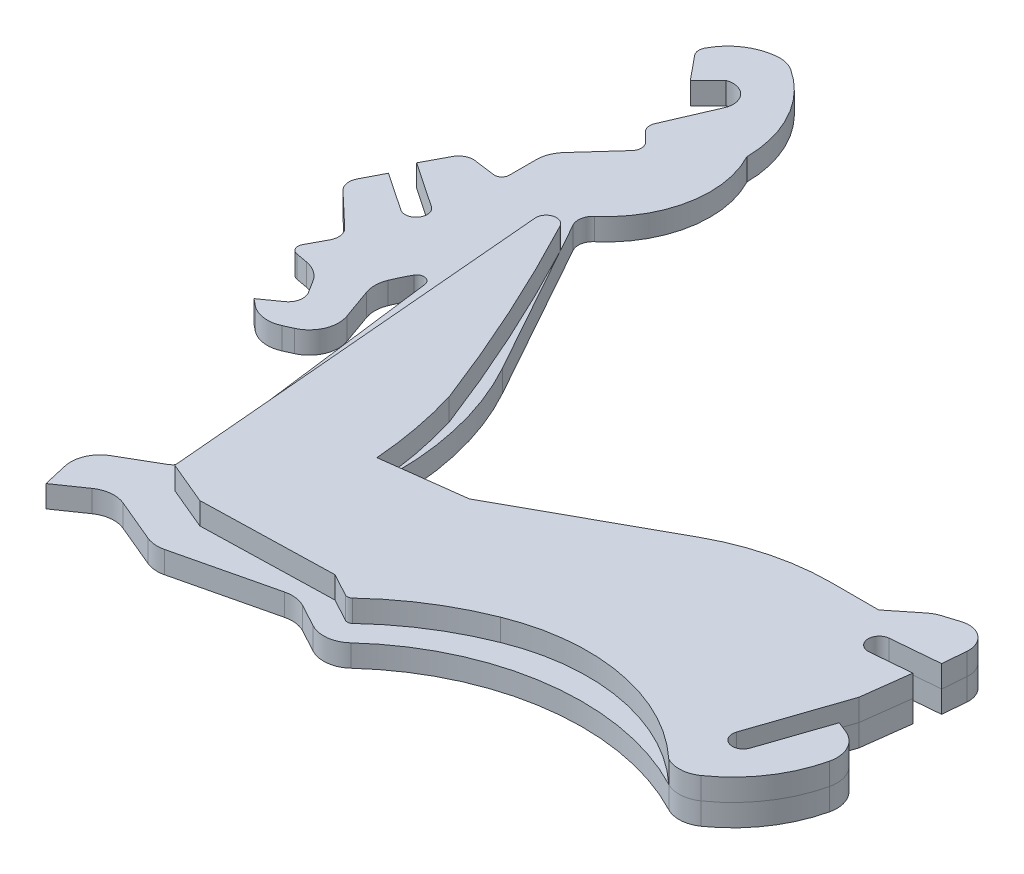
SolidWorks part; units mm, degrees
ref_plane "Front Plane" through (0, 0, 0) normal (0, 0, 1) x (1, 0, 0)
ref_plane "Top Plane" through (0, 0, 0) normal (0, 1, 0) x (1, 0, 0)
ref_plane "Right Plane" through (0, 0, 0) normal (1, 0, 0) x (0, 0, -1)
sketch "Sketch2" plane through (0, 0, 0) normal (0, 1, 0) x (1, 0, 0)
  line L0 (104.8617, 51.61) -> (96.2857, 51.61)
  line L1 (96.2857, 48.61) -> (104.8617, 48.61)
  line L2 (104.8617, 48.61) -> (104.8617, 42.36)
  line L3 (107.0706, 39.34) -> (104.0266, 29.4584)
  line L4 (101.1595, 30.3416) -> (104.8617, 42.36)
  line L5 (105.5312, 18.3607) -> (111.09, 27.1258)
  line L6 (104.8617, 51.61) -> (107.0706, 55.46)
  line L7 (89.7728, 69.8362) -> (57.4, 86.17)
  line L8 (41.6529, 73.6621) -> (36.03, 31.3784)
  line L9 (36.03, 31.3784) -> (29.1482, 28.9869)
  line L10 (29.1482, 28.9869) -> (21.9915, 21.0198)
  line L11 (21.9915, 21.0198) -> (8.1869, 15.1615)
  line L12 (0, 0) -> (0, 4.28)
  line L13 (0, 4.28) -> (8.2554, 5.2)
  line L14 (7.9231, 8.1815) -> (-3.1214, 6.9507)
  line L15 (-3.1214, 6.9507) -> (-7.4992, 8.4826)
  line L16 (-7.4992, 8.4826) -> (-11.8276, 7.2216)
  line L17 (-11.8276, 7.2216) -> (-19.2552, 11.2976)
  line L18 (-19.2552, 11.2976) -> (-23.2053, 10.8574)
  line L19 (-23.2053, 10.8574) -> (-22.2697, 7.6463)
  line L20 (-22.2697, 7.6463) -> (-24.8125, 7.2216)
  line L21 (0, 0) -> (20.16, 0)
  line L22 (20.16, 0) -> (27.0155, 3.9247)
  line L23 (27.0155, 3.9247) -> (38.9, -1.2)
  line L24 (38.9, -1.2) -> (41.66, 2.4827)
  line L25 (41.66, 2.4827) -> (45.9, 1.9915)
  line L26 (45.9, 1.9915) -> (46.4657, 5.8541)
  line L27 (25.83, 11.99) -> (49.95, 19.39)
  line L28 (49.95, 19.39) -> (57.13, 16.32)
  line L29 (57.13, 16.32) -> (61.9358, 23.0276)
  line L30 (61.9358, 23.0276) -> (67.6517, 44.29)
  arc A0 (96.2857, 51.61) -> (96.2857, 48.61) centre (96.2857, 50.11) ccw
  arc A1 (107.0706, 39.34) -> (111.09, 27.1258) centre (97.2099, 29.3266) cw
  arc A2 (104.0266, 29.4584) -> (101.1595, 30.3416) centre (102.5931, 29.9) cw
  arc A3 (107.0706, 55.46) -> (93.2591, 66.4439) centre (93.6334, 52.7391) ccw
  arc A4 (93.2591, 66.4439) -> (89.7728, 69.8362) centre (93.1665, 69.8362) cw
  arc A5 (57.4, 86.17) -> (41.6529, 73.6621) centre (56.0104, 71.7528) ccw
  arc A6 (8.1869, 15.1615) -> (-17.7049, 14.5311) centre (-5.6083, 49.7338) cw
  arc A7 (8.2554, 5.2) -> (7.9231, 8.1815) centre (8.0892, 6.6908) ccw
  arc A8 (-24.8125, 7.2216) -> (-27.5, 15.12) centre (-19.6156, 13.3963) cw
  arc A9 (-27.5, 15.12) -> (-17.7049, 14.5311) centre (-22.91, 9.71) cw
  arc A10 (46.4657, 5.8541) -> (26.4315, 9.0647) centre (30.5748, -29.1928) ccw
  arc A11 (26.4315, 9.0647) -> (25.83, 11.99) centre (26.27, 10.556) cw
  arc A12 (67.6517, 44.29) -> (105.5312, 18.3607) centre (122.4523, 83.7134) ccw
  point P4 (0, 0)
  point P9 (102.1515, 28.4665)
  point P12 (94.7857, 50.11)
  point P13 (-27.5, 15.12)
  point P72 (9.58, 6.8569)
  dimension "D6" = 1.5
  dimension "D11" = 1.5
  dimension "D32" = 14.0535
  dimension "D33" = 13.7098
  dimension "D34" = 3.3937
  dimension "D35" = 14.484
  dimension "D36" = 37.223
  dimension "D37" = 8.0706
  dimension "D38" = 7.0948
  dimension "D39" = 38.4812
  dimension "D40" = 67.5078
  dimension "D75" = 1.5
  dimension "D1" = 51.61
  dimension "D2" = 111.09
  dimension "D3" = 10.076
  dimension "D4" = 27.5
  dimension "D5" = 15.12
  dimension "D7" = 29.9
  dimension "D8" = 39.34
  dimension "D9" = 6.25
  dimension "D10" = 102.5931
  dimension "D12" = 4.28
  dimension "D13" = 20.16
  dimension "D14" = 5.14
  dimension "D15" = 1.2
  dimension "D16" = 45.9
  dimension "D17" = 38.9
  dimension "D18" = 86.17
  dimension "D19" = 9.58
  dimension "D20" = 5.2
  dimension "D21" = 11.99
  dimension "D22" = 16.32
  dimension "D23" = 57.13
  dimension "D24" = 49.95
  dimension "D25" = 26.27
  dimension "19.39" = 19.39
  dimension "D26" = 84.9
  dimension "D27" = 63.53
  dimension "D28" = 37.21
  dimension "D29" = 44.29
  dimension "D30" = 3.85
  dimension "D31" = 20
  dimension "D41" = 8.1869
  dimension "D42" = 21.9915
  dimension "D43" = 26.4315
  dimension "D44" = 27.0155
  dimension "D45" = 29.1482
  dimension "D46" = 41.6529
  dimension "D47" = 41.66
  dimension "D48" = 46.4657
  dimension "D49" = 56.0104
  dimension "D50" = 61.9358
  dimension "D51" = 67.6517
  dimension "D52" = 89.7728
  dimension "D53" = 97.2099
  dimension "D54" = 105.5312
  dimension "D55" = 122.4523
  dimension "D56" = 3.1214
  dimension "D57" = 5.6083
  dimension "D58" = 7.4992
  dimension "D59" = 11.8276
  dimension "D60" = 17.7049
  dimension "D61" = 19.2552
  dimension "D62" = 19.6156
  dimension "D63" = 22.2697
  dimension "D64" = 22.91
  dimension "D65" = 23.2053
  dimension "D66" = 24.8125
  dimension "D67" = 1.9915
  dimension "D68" = 2.4827
  dimension "D69" = 7.6463
  dimension "D70" = 8.4826
  dimension "D71" = 11.2976
  dimension "D72" = 21.0198
  dimension "D73" = 23.0276
  dimension "D74" = 28.9869
sketch "Sketch3" plane through (0, 0, 0) normal (0, 1, 0) x (1, 0, 0)
  line L0 (7.9231, 8.1815) -> (1.2884, 7.4422)
  line L1 (45.9, 1.9915) -> (46.4657, 5.8541) construction
  line L2 (41.66, 2.4827) -> (45.9, 1.9915) construction
  line L3 (38.9, -1.2) -> (41.66, 2.4827) construction
  line L4 (27.0155, 3.9247) -> (38.9, -1.2) construction
  line L5 (20.16, 0) -> (27.0155, 3.9247) construction
  line L6 (0, 4.28) -> (8.2554, 5.2) construction
  line L7 (0, 0) -> (0, 4.28) construction
  line L8 (0, 0) -> (20.16, 0) construction
  line L9 (1.2884, 7.4422) -> (2.7682, 14.19)
  line L10 (45.9, 1.9915) -> (46.4657, 5.8541)
  line L11 (41.66, 2.4827) -> (45.9, 1.9915)
  line L12 (38.9, -1.2) -> (41.66, 2.4827)
  line L13 (27.0155, 3.9247) -> (38.9, -1.2)
  line L14 (20.16, 0) -> (27.0155, 3.9247)
  line L15 (0, 4.28) -> (8.2554, 5.2)
  line L16 (0, 0) -> (0, 4.28)
  line L17 (0, 0) -> (20.16, 0)
  line L18 (-19.3597, 16.8) -> (-22.2168, 13.6663)
  line L19 (-22.2168, 13.6663) -> (-24.8203, 14.623)
  line L20 (-24.8203, 14.623) -> (-22.6465, 20.5386)
  line L21 (-22.6465, 20.5386) -> (-15.7038, 22.1118)
  line L22 (-15.7038, 22.1118) -> (-10.0733, 18.8185)
  line L23 (-10.0733, 18.8185) -> (-5.1865, 19.8808)
  line L24 (-5.1865, 19.8808) -> (12.13, 16.8)
  line L25 (12.13, 16.8) -> (38.76, 34.29)
  line L26 (87.31, 93.5914) -> (80.7227, 93.015)
  line L27 (80.9841, 90.0265) -> (86.4632, 90.5058)
  line L28 (87.31, 93.5914) -> (87.31, 111.63)
  line L29 (87.31, 111.63) -> (66.29, 103.0079)
  line L32 (66.29, 103.0079) -> (64.5523, 69.7569)
  line L33 (64.5523, 69.7569) -> (56.0586, 66.407)
  line L34 (56.0586, 66.407) -> (44.7, 32)
  line L35 (44.7, 32) -> (38.76, 34.29)
  line L36 (25.83, 11.99) -> (54.05, 24.15)
  line L37 (54.05, 24.15) -> (66.29, 24.15)
  line L38 (68.0387, 28.663) -> (60.2978, 29.686)
  line L39 (87.31, 79.61) -> (91.6185, 77.8876)
  line L40 (87.31, 79.61) -> (84.2303, 70.5437)
  line L41 (81.3897, 71.5086) -> (85.6329, 84)
  line L42 (85.6329, 84) -> (86.4632, 90.5058)
  arc A0 (25.83, 11.99) -> (26.4315, 9.0647) centre (26.27, 10.556) ccw construction
  arc A1 (46.4657, 5.8541) -> (26.4315, 9.0647) centre (30.5748, -29.1928) ccw construction
  arc A3 (25.83, 11.99) -> (26.4315, 9.0647) centre (26.27, 10.556) ccw
  arc A4 (46.4657, 5.8541) -> (26.4315, 9.0647) centre (30.5748, -29.1928) ccw
  arc A5 (8.2554, 5.2) -> (7.9231, 8.1815) centre (8.0892, 6.6908) ccw
  arc A6 (2.7682, 14.19) -> (-19.3597, 16.8) centre (-1.1426, 76.1401) cw
  arc A7 (80.7227, 93.015) -> (80.9841, 90.0265) centre (80.8534, 91.5207) ccw
  arc A8 (66.29, 24.15) -> (68.0387, 28.663) centre (61.3409, 28.663) ccw
  arc A9 (60.2978, 29.686) -> (80.9841, 62.2084) centre (34.8127, 68.7363) ccw
  arc A10 (91.6185, 77.8876) -> (80.9841, 62.2084) centre (74.0824, 78.3355) cw
  arc A11 (84.2303, 70.5437) -> (81.3897, 71.5086) centre (82.81, 71.0261) cw
  point P20 (87.31, 111.63)
  point P28 (87.31, 79.61)
  point P40 (79.3591, 91.39)
  point P55 (0, 2.14)
  point P77 (9.58, 6.8569)
  point P90 (82.3275, 69.6058)
  dimension "D5" = 1.5
  dimension "D22" = 62.0734
  dimension "D23" = 6.6978
  dimension "D24" = 46.6306
  dimension "D25" = 17.5418
  dimension "D1" = 111.63
  dimension "D2" = 87.31
  dimension "D3" = 79.61
  dimension "D4" = 17.97
  dimension "D6" = 8.25
  dimension "95" = 95
  dimension "D7" = 54.05
  dimension "D8" = 44.7
  dimension "D9" = 32
  dimension "D10" = 24.15
  dimension "D11" = 16.8
  dimension "D12" = 2.55
  dimension "D13" = 38.76
  dimension "D14" = 2.29
  dimension "D15" = 66.29
  dimension "D16" = 4.64
  dimension "D17" = 23.46
  dimension "D18" = 82.81
  dimension "D19" = 84
  dimension "D20" = 5.5
  dimension "D21" = 14.19
  dimension "D26" = 1.2884
  dimension "D27" = 2.7682
  dimension "D28" = 34.8127
  dimension "D29" = 56.0586
  dimension "D30" = 60.2978
  dimension "D31" = 61.3409
  dimension "D32" = 64.5523
  dimension "D33" = 68.0387
  dimension "D34" = 74.0824
  dimension "D35" = 1.1426
  dimension "D36" = 13.6663
  dimension "D37" = 14.623
  dimension "D38" = 91.6185
  dimension "D39" = 18.8185
  dimension "D40" = 5.1865
  dimension "D41" = 10.0733
  dimension "D42" = 15.7038
  dimension "D43" = 19.8808
  dimension "D44" = 22.2168
  dimension "D45" = 22.6465
  dimension "D46" = 24.8203
  dimension "D48" = 22.1118
  dimension "D49" = 66.407
  dimension "D51" = 69.7569
  dimension "D53" = 103.0079
sketch "Sketch4" plane through (0, 0, 0) normal (0, 1, 0) x (1, 0, 0)
  line L0 (87.31, 79.61) -> (91.6185, 77.8876) construction
  line L1 (87.31, 79.61) -> (84.2303, 70.5437) construction
  line L2 (81.3897, 71.5086) -> (85.6329, 84) construction
  line L3 (85.6329, 84) -> (86.4632, 90.5058) construction
  line L4 (87.31, 93.5914) -> (80.7227, 93.015) construction
  line L5 (80.9841, 90.0265) -> (86.4632, 90.5058) construction
  line L6 (87.31, 79.61) -> (91.6185, 77.8876)
  line L7 (87.31, 79.61) -> (84.2303, 70.5437)
  line L8 (81.3897, 71.5086) -> (85.6329, 84)
  line L9 (85.6329, 84) -> (86.4632, 90.5058)
  line L10 (87.31, 93.5914) -> (80.7227, 93.015)
  line L11 (80.9841, 90.0265) -> (86.4632, 90.5058)
  line L12 (87.31, 93.5914) -> (87.9384, 101.2314)
  line L13 (87.9384, 101.2314) -> (80.8847, 99.0137)
  line L14 (80.8847, 99.0137) -> (76.6618, 95.6406)
  line L15 (76.6618, 95.6406) -> (62.4514, 95.6406)
  line L16 (62.4514, 95.6406) -> (35.6224, 80.8332)
  line L17 (35.6224, 80.8332) -> (24.4232, 79.3958)
  line L18 (24.4232, 79.3958) -> (24.4232, 92.5302)
  line L19 (24.4232, 92.5302) -> (6.4632, 124.7958)
  line L20 (39.5557, 56.754) -> (32.4992, 60.5705)
  line L21 (32.4992, 60.5705) -> (16.5173, 56.754)
  line L22 (16.5173, 56.754) -> (7.4148, 60.5705)
  line L23 (7.4148, 60.5705) -> (1.8925, 56.754)
  line L24 (1.8925, 56.754) -> (0.4632, 62.9924)
  line L25 (0.4632, 62.9924) -> (9.066, 67.9678)
  line L26 (9.066, 67.9678) -> (3.8794, 108.8404)
  line L27 (0.6632, 102.6159) -> (3.8794, 93.5914)
  line L28 (3.8794, 93.5914) -> (-2.9368, 90.5058)
  line L29 (-2.9368, 90.5058) -> (-5.7689, 92.8083)
  line L30 (-5.7689, 92.8083) -> (-1.7781, 95.6406)
  line L31 (-1.7781, 95.6406) -> (-4.7653, 100.4083)
  line L32 (-4.7653, 100.4083) -> (-9.4961, 101.2694)
  line L33 (-9.4961, 101.2694) -> (-6.8152, 106.2905)
  line L34 (-6.8152, 106.2905) -> (-13.5555, 112.677)
  line L35 (-13.5555, 112.677) -> (-11.4183, 116.8058)
  line L36 (-11.4183, 116.8058) -> (-6.2216, 113.3058)
  line L37 (-4.5458, 115.7941) -> (-10.725, 119.9558)
  line L38 (-10.725, 119.9558) -> (-8.366, 124.3875)
  line L39 (-8.366, 124.3875) -> (-2.9368, 123.667)
  line L40 (-2.9368, 123.667) -> (-2.9368, 130.0558)
  line L41 (-2.9368, 130.0558) -> (3.4131, 137.0856)
  line L42 (3.4131, 137.0856) -> (0.5228, 139.9564)
  line L43 (0.5228, 139.9564) -> (3.6981, 147.3182)
  line L44 (0.6632, 150.8114) -> (-1.7781, 148.37)
  line L45 (-1.7781, 148.37) -> (-4.9998, 152.3019)
  arc A0 (-6.2216, 113.3058) -> (-4.5458, 115.7941) centre (-5.3837, 114.5499) ccw
  arc A1 (81.3897, 71.5086) -> (84.2303, 70.5437) centre (82.81, 71.0261) ccw construction
  arc A2 (80.7227, 93.015) -> (80.9841, 90.0265) centre (80.8534, 91.5207) ccw construction
  arc A3 (91.6185, 77.8876) -> (81.8558, 62.61) centre (74.0824, 78.3355) cw
  arc A4 (81.3897, 71.5086) -> (84.2303, 70.5437) centre (82.81, 71.0261) ccw
  arc A5 (80.7227, 93.015) -> (80.9841, 90.0265) centre (80.8534, 91.5207) ccw
  arc A6 (80.9841, 62.2084) -> (91.6185, 77.8876) centre (74.0824, 78.3355) ccw construction
  arc A7 (81.8558, 62.61) -> (39.5557, 56.754) centre (64.2679, 33.9509) ccw
  arc A8 (3.8794, 108.8404) -> (0.6632, 102.6159) centre (21.1237, 95.9873) ccw
  arc A9 (6.4632, 124.7958) -> (11.0968, 143.2092) centre (-1.4543, 136.5779) ccw
  arc A10 (11.0968, 143.2092) -> (2.7832, 157.1114) centre (-4.9998, 143.0202) ccw
  arc A11 (3.6981, 147.3182) -> (0.6632, 150.8114) centre (1.4835, 148.4591) ccw
  arc A12 (-4.9998, 152.3019) -> (2.7832, 157.1114) centre (1.9469, 149.7625) cw
  point P0 (91.6185, 77.8876)
  point P22 (2.7832, 157.1114)
  point P24 (0.6632, 150.8114)
  point P25 (-2.9368, 90.5058)
  point P26 (24.4232, 79.3958)
  point P27 (6.4632, 124.7958)
  point P31 (37.6632, 57.2558)
  dimension "D18" = 0.5228
  dimension "D22" = 33.6255
  dimension "D23" = 21.5075
  dimension "D24" = 14.1952
  dimension "D25" = 16.0977
  dimension "D26" = 2.4912
  dimension "D27" = 7.3963
  dimension "D1" = 7.64
  dimension "D2" = 62.04
  dimension "D3" = 11.11
  dimension "D4" = 34.29
  dimension "D5" = 80
  dimension "D6" = 63.52
  dimension "D7" = 83.68
  dimension "D8" = 2.12
  dimension "D9" = 6.3
  dimension "D10" = 17
  dimension "D11" = 48.8
  dimension "D12" = 33.25
  dimension "D13" = 89.4
  dimension "D14" = 3.65
  dimension "D15" = 26.3
  dimension "D16" = 29.45
  dimension "D17" = 7.45
  dimension "D19" = 22.8
  dimension "D20" = 86
  dimension "D21" = 6.4
  dimension "D28" = 1.4835
  dimension "D29" = 1.8925
  dimension "D30" = 1.9469
  dimension "D31" = 3.4131
  dimension "D32" = 3.6981
  dimension "D33" = 3.8794
  dimension "D34" = 7.4148
  dimension "D35" = 9.066
  dimension "D36" = 11.0968
  dimension "D37" = 16.5173
  dimension "D38" = 21.1237
  dimension "D39" = 32.4992
  dimension "D40" = 35.6224
  dimension "D41" = 39.5557
  dimension "D42" = 62.4514
  dimension "D43" = 64.2679
  dimension "D44" = 76.6618
  dimension "D45" = 80.8847
  dimension "D46" = 87.9384
  dimension "D47" = 1.4543
  dimension "D48" = 1.7781
  dimension "D49" = 4.5458
  dimension "D50" = 4.7653
  dimension "D51" = 60.5705
  dimension "D52" = 67.9678
  dimension "D53" = 5.7689
  dimension "D54" = 80.8332
  dimension "D55" = 6.8152
  dimension "D56" = 8.366
  dimension "D57" = 9.4961
  dimension "D58" = 92.5302
  dimension "D59" = 93.5914
  dimension "D60" = 13.5555
  dimension "D61" = 95.6406
  dimension "D62" = 95.9873
  dimension "D63" = 99.0137
  dimension "D64" = 100.4083
  dimension "D65" = 101.2694
  dimension "D67" = 106.2905
  dimension "D69" = 112.677
  dimension "D70" = 123.667
  dimension "D71" = 124.3875
  dimension "D72" = 130.0558
  dimension "D73" = 137.0856
  dimension "D74" = 139.9564
  dimension "D75" = 148.37
extrude "Boss-Extrude2" add sketch "Sketch4" along normal blind 3
fillet "Fillet1" radius 1 3 edges at (3.8794, 1.5, -108.8404) (-9.4961, 1.5, -101.2694) (-2.9368, 1.5, -123.667)
fillet "Fillet2" radius 4 14 edges at (81.8558, 1.5, -62.61) (0.4632, 1.5, -62.9924) (16.5173, 1.5, -56.754) (7.4148, 1.5, -60.5705) (32.4992, 1.5, -60.5705) (39.5557, 1.5, -56.754) (-2.9368, 1.5, -130.0558) (-4.7653, 1.5, -100.4083) (0.6632, 1.5, -102.6159) (-2.9368, 1.5, -90.5058) (3.8794, 1.5, -93.5914) (80.8847, 1.5, -99.0137) (91.6185, 1.5, -77.8876) (2.7832, 1.5, -157.1114)
fillet "Fillet3" radius 40 1 edges at (24.4232, 1.5, -92.5302)
fillet "Fillet4" radius 2 6 edges at (-6.8152, 1.5, -106.2905) (-1.7781, 1.5, -95.6406) (9.066, 1.5, -67.9678) (-8.366, 1.5, -124.3875) (-13.5555, 1.5, -112.677) (6.4632, 1.5, -124.7958)
fillet "Fillet5" radius 1.4 3 edges at (-4.9998, 1.5, -152.3019) (0.5228, 1.5, -139.9564) (3.4131, 1.5, -137.0856)
fillet "Fillet6" radius 30 1 edges at (62.4514, 1.5, -95.6406)
fillet "Fillet7" radius 3 1 edges at (87.9384, 1.5, -101.2314)
sketch "Sketch5" plane through (0, 3, 0) normal (0, 1, 0) x (1, 0, 0)
  line L0 (87.31, 79.61) -> (84.2303, 70.5437) construction
  line L1 (88.7674, 79.0274) -> (87.31, 79.61) construction
  line L2 (87.31, 79.61) -> (84.2303, 70.5437)
  line L3 (88.7674, 79.0274) -> (87.31, 79.61)
  line L4 (81.3897, 71.5086) -> (85.6329, 84) construction
  line L5 (86.4632, 90.5058) -> (80.9841, 90.0265) construction
  line L6 (85.6329, 84) -> (86.4632, 90.5058) construction
  line L7 (81.3897, 71.5086) -> (85.6329, 84)
  line L8 (86.4632, 90.5058) -> (80.9841, 90.0265)
  line L9 (85.6329, 84) -> (86.4632, 90.5058)
  line L10 (80.3008, 98.5473) -> (76.6618, 95.6406) construction
  line L11 (83.6831, 99.8935) -> (81.5975, 99.2378) construction
  line L12 (87.31, 93.5914) -> (87.5727, 96.7857) construction
  line L13 (80.7227, 93.015) -> (87.31, 93.5914) construction
  line L14 (80.3008, 98.5473) -> (76.6618, 95.6406)
  line L15 (83.6831, 99.8935) -> (81.5975, 99.2378)
  line L16 (87.31, 93.5914) -> (87.5727, 96.7857)
  line L17 (80.7227, 93.015) -> (87.31, 93.5914)
  line L18 (35.6224, 80.8332) -> (24.4232, 79.3958) construction
  line L19 (55.6845, 91.9058) -> (35.6224, 80.8332) construction
  line L20 (76.6618, 95.6406) -> (70.1806, 95.6406) construction
  line L21 (35.6224, 80.8332) -> (24.4232, 79.3958)
  line L22 (55.6845, 91.9058) -> (35.6224, 80.8332)
  line L23 (76.6618, 95.6406) -> (70.1806, 95.6406)
  line L26 (35.3901, 62.7018) -> (38.4867, 61.0271)
  line L27 (35.3901, 62.7018) -> (38.4867, 61.0271)
  line L28 (35.3901, 62.7018) -> (17.4004, 62.2392)
  line L29 (11.5222, 64.7038) -> (17.4004, 62.2392)
  line L30 (11.5222, 64.7038) -> (17.4004, 62.2392)
  line L31 (11.5222, 64.7038) -> (6.8931, 118.4946)
  line L32 (19.3736, 101.602) -> (7.3061, 123.2816) construction
  line L33 (24.4232, 79.3958) -> (24.4232, 82.1476) construction
  arc A0 (84.1158, 63.9463) -> (91.1817, 74.4204) centre (74.0824, 78.3355) ccw construction
  arc A1 (91.1817, 74.4204) -> (88.7674, 79.0274) centre (87.2826, 75.3132) ccw construction
  arc A2 (84.1158, 63.9463) -> (91.1817, 74.4204) centre (74.0824, 78.3355) ccw
  arc A3 (91.1817, 74.4204) -> (88.7674, 79.0274) centre (87.2826, 75.3132) ccw
  arc A4 (81.3897, 71.5086) -> (84.2303, 70.5437) centre (82.81, 71.0261) ccw construction
  arc A5 (81.3897, 71.5086) -> (84.2303, 70.5437) centre (82.81, 71.0261) ccw
  arc A6 (81.5975, 99.2378) -> (80.3008, 98.5473) centre (82.7972, 95.422) ccw construction
  arc A7 (87.5727, 96.7857) -> (83.6831, 99.8935) centre (84.5828, 97.0316) ccw construction
  arc A8 (80.7227, 93.015) -> (80.9841, 90.0265) centre (80.8534, 91.5207) ccw construction
  arc A9 (81.5975, 99.2378) -> (80.3008, 98.5473) centre (82.7972, 95.422) ccw
  arc A10 (87.5727, 96.7857) -> (83.6831, 99.8935) centre (84.5828, 97.0316) ccw
  arc A11 (80.7227, 93.015) -> (80.9841, 90.0265) centre (80.8534, 91.5207) ccw
  arc A12 (70.1806, 95.6406) -> (55.6845, 91.9058) centre (70.1806, 65.6406) ccw construction
  arc A13 (70.1806, 95.6406) -> (55.6845, 91.9058) centre (70.1806, 65.6406) ccw
  arc A14 (79.9611, 63.6898) -> (84.1158, 63.9463) centre (81.8279, 67.2274) ccw construction
  arc A15 (79.9611, 63.6898) -> (84.1158, 63.9463) centre (81.8279, 67.2274) ccw
  arc A16 (79.9611, 63.6898) -> (51.6831, 68.9739) centre (61.6955, 44.248) ccw
  arc A19 (51.6831, 68.9739) -> (39.3503, 61.1339) centre (65.9783, 32.8664) ccw
  arc A20 (38.4867, 61.0271) -> (39.3503, 61.1339) centre (38.8435, 61.6867) ccw
  arc A21 (38.4867, 61.0271) -> (39.3503, 61.1339) centre (38.8435, 61.6867) ccw
  arc A23 (6.8931, 118.4946) -> (9.5376, 119.2726) centre (8.2943, 118.6152) cw
  arc A24 (24.4232, 79.3958) -> (22.152, 91.5207) centre (-33.7731, 74.7698) ccw
  arc A25 (22.152, 91.5207) -> (9.5376, 119.2726) centre (-215.9626, 0.0303) ccw
  point P18 (6.4211, 119.1564)
  point P45 (20.5589, 94.8163)
  point P47 (0, 0)
  point P48 (0, 0)
  point P49 (9.4296, 115.6657)
  point P50 (7.2868, 118.0619)
  point P51 (0, 0)
  point P52 (0, 0)
  point P53 (8.2371, 118.2026)
  point P54 (0, 0)
  point P55 (0, 0)
  point P57 (8.3161, 118.3969)
  point P59 (20.3636, 90.0265)
  point P60 (22.152, 91.5207)
  point P61 (0, 0)
  point P64 (0, 0)
  dimension "D3" = 26.6761
  dimension "D4" = 38.8343
  dimension "D5" = 1.4064
  dimension "D6" = 58.3799
  dimension "D7" = 255.0864
  dimension "D1" = 3.25
  dimension "D8" = 27.2599
  dimension "D10" = 37.2722
  dimension "D11" = 2.2712
  dimension "D12" = 14.8856
  dimension "D13" = 16.1289
  dimension "D2" = 5.4
extrude "Boss-Extrude3" add sketch "Sketch5" along normal blind 3 separate body
